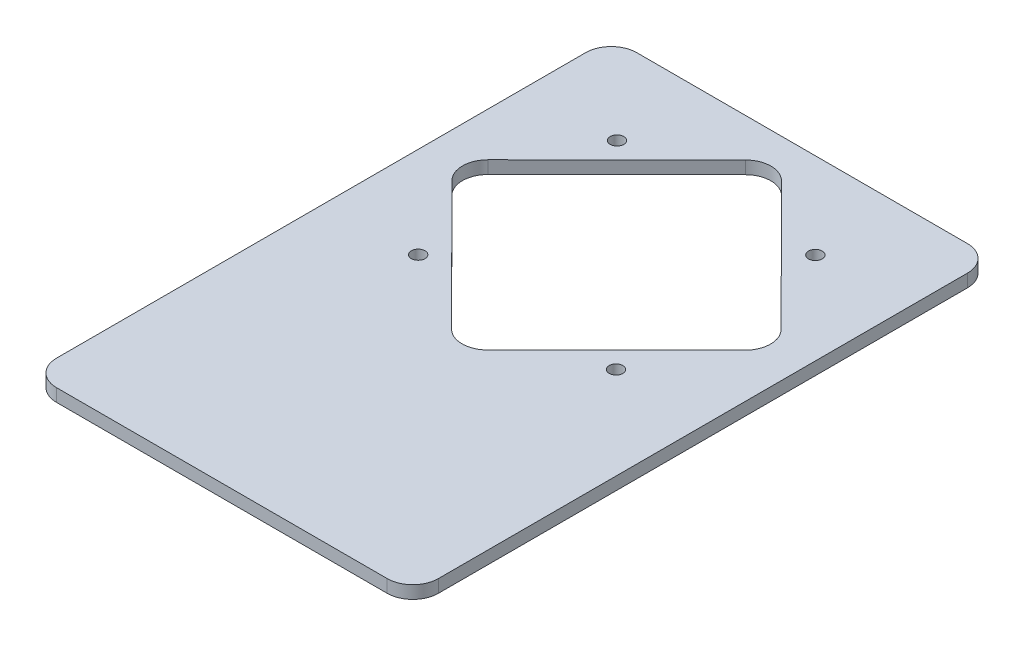
SolidWorks part; units mm, degrees
material "Acrylic (Medium-high impact)"
ref_plane "Front Plane" through (0, 0, 0) normal (0, 0, 1) x (1, 0, 0)
ref_plane "Top Plane" through (0, 0, 0) normal (0, 1, 0) x (1, 0, 0)
ref_plane "Right Plane" through (0, 0, 0) normal (1, 0, 0) x (0, 0, -1)
sketch "Sketch1" plane through (0, 0, 0) normal (0, 1, 0) x (1, 0, 0)
  line L1 (0, 138.4911) -> (94.832, 138.4911)
  line L2 (6.4298, 92.5223) -> (47.416, 133.3837)
  line L3 (0, 138.4911) -> (0, -5.6139)
  line L4 (0, -5.6139) -> (94.832, -5.6139)
  line L5 (94.832, 138.4911) -> (94.832, -5.6139)
  line L16 (6.4298, 92.5223) -> (47.2912, 51.5361)
  line L17 (47.2912, 51.5361) -> (88.2774, 92.3975)
  line L19 (88.2774, 92.3975) -> (47.416, 133.3837)
  circle A0 centre (22.7875, 117.1508) radius 1.7
  circle A1 centre (72.0445, 117.1508) radius 1.7
  circle A2 centre (71.9197, 67.769) radius 1.7
  circle A3 centre (22.6627, 67.8938) radius 1.7
  point P11 (67.8467, 112.8906)
  point P13 (0, 0)
  point P14 (0, 0)
  point P15 (0, 0)
  point P16 (0, 0)
  point P17 (0, 0)
  dimension "D1" = 57.15
  dimension "D6" = 3.4
  dimension "D7" = 49.257
  dimension "D8" = 24.6285
  dimension "D9" = 49.257
  dimension "D10" = 24.6285
  dimension "D11" = 49.257
  dimension "D13" = 24.6285
  dimension "D2" = 94.832
  dimension "D3" = 144.105
  dimension "D4" = 57.875
  dimension "D5" = 57.875
  dimension "D12" = 24.6285
extrude "Boss-Extrude2" add sketch "Sketch1" along normal blind 3.175
fillet "Fillet1" radius 6.35 4 edges at (47.2912, 1.5875, -51.5361) (88.2774, 1.5875, -92.3975) (47.416, 1.5875, -133.3837) (6.4298, 1.5875, -92.5223)
fillet "Fillet2" radius 6.35 4 edges at (0, 1.5875, -138.4911) (94.832, 1.5875, -138.4911) (0, 1.5875, 5.6139) (94.832, 1.5875, 5.6139)
